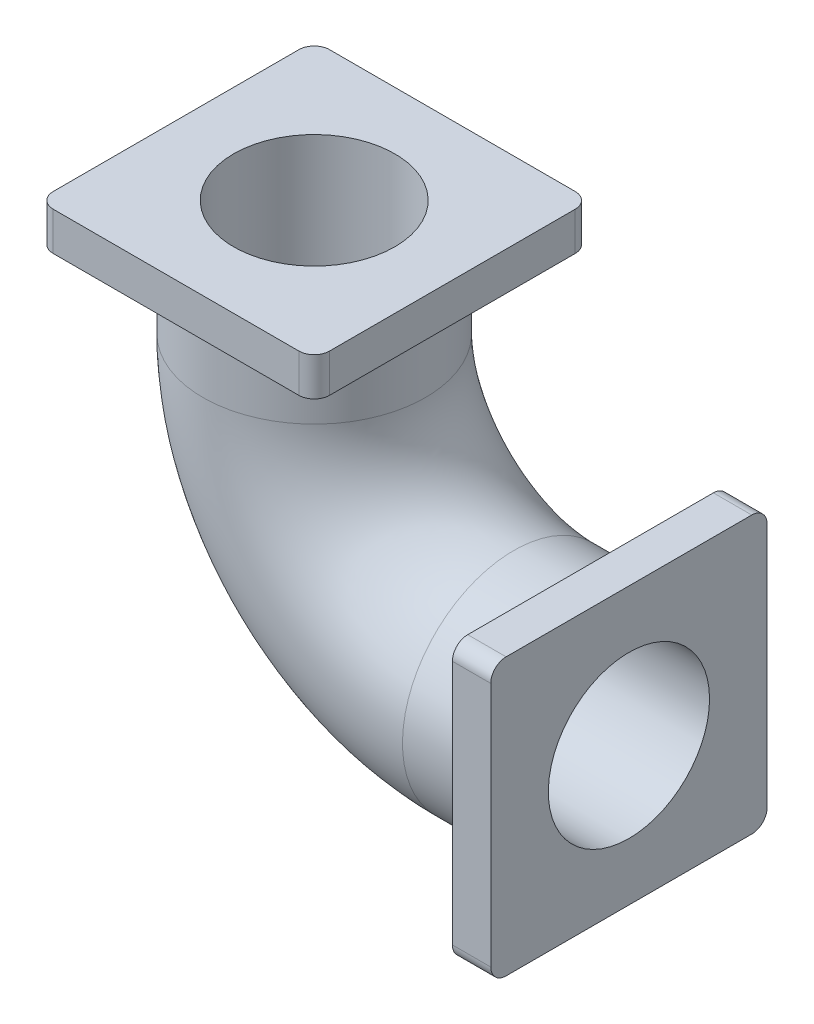
SolidWorks part; units mm, degrees
material "Ductile Iron"
ref_plane "Front Plane" through (0, 0, 0) normal (0, 0, 1) x (1, 0, 0)
ref_plane "Top Plane" through (0, 0, 0) normal (0, 1, 0) x (1, 0, 0)
ref_plane "Right Plane" through (0, 0, 0) normal (1, 0, 0) x (0, 0, -1)
sketch "Sketch2" plane through (0, 0, 0) normal (0, 0, 1) x (1, 0, 0)
  line L0 (0, 0) -> (-150, 0)
  line L1 (-410, 260) -> (-410, 410)
  arc A0 (-150, 0) -> (-410, 260) centre (-150, 260) cw
  dimension "D2" = 260
  dimension "D1" = 150
sketch "Sketch3" plane through (0, 0, 0) normal (1, 0, 0) x (0, 0, -1)
  circle A0 centre (0, 0) radius 145
  dimension "D1" = 290
sweep "Sweep-Thin1" add profiles "Sketch3" path "Sketch2" parameters "D1"=40
sketch "Sketch4" plane through (0, 0, 0) normal (1, 0, 0) x (0, 0, -1)
  line L1 (-180, -180) -> (180, -180)
  line L2 (-180, -180) -> (-180, 180)
  line L3 (-180, 180) -> (180, 180)
  line L4 (180, -180) -> (180, 180)
  line L5 (-180, -180) -> (180, 180) construction
  line L6 (-180, 180) -> (180, -180) construction
  point P0 (0, 0)
  circle M4 centre (0, 0) radius 145
  dimension "D1" = 360
  dimension "D2" = 360
extrude "Boss-Extrude1" add sketch "Sketch4" against normal blind 50 contours L1 L4 L3 L2 M4
fillet "Fillet1" radius 20 4 edges at (-25, -180, -180) (-25, -180, 180) (-25, 180, -180) (-25, 180, 180)
sketch "Sketch6" plane through (0, 410, 0) normal (0, 1, 0) x (1, 0, 0)
  line L1 (-590, -180) -> (-230, -180)
  line L2 (-590, -180) -> (-590, 180)
  line L3 (-590, 180) -> (-230, 180)
  line L4 (-230, -180) -> (-230, 180)
  line L5 (-590, -180) -> (-230, 180) construction
  line L6 (-590, 180) -> (-230, -180) construction
  point P0 (-410, 0)
  circle M4 centre (-410, 0) radius 145
  dimension "D1" = 360
  dimension "D2" = 360
extrude "Boss-Extrude2" add sketch "Sketch6" against normal blind 50 contours L1 L4 L3 L2 M4
fillet "Fillet2" radius 20 4 edges at (-590, 385, 180) (-230, 385, 180) (-590, 385, -180) (-230, 385, -180)
sketch "Sketch7" plane through (0, 0, 0) normal (1, 0, 0) x (0, 0, -1)
  line L1 (-130, -130) -> (130, -130) construction
  line L2 (-130, -130) -> (-130, 130) construction
  line L3 (-130, 130) -> (130, 130) construction
  line L4 (130, -130) -> (130, 130) construction
  line L5 (-130, -130) -> (130, 130) construction
  line L6 (-130, 130) -> (130, -130) construction
  circle A0 centre (-130, 130) radius 30
  point P0 (0, 0)
  dimension "D1" = 60
  dimension "D2" = 260
  dimension "D3" = 260
extrude "Boss-Extrude4" add sketch "Sketch7" against normal blind 10 contours A0
